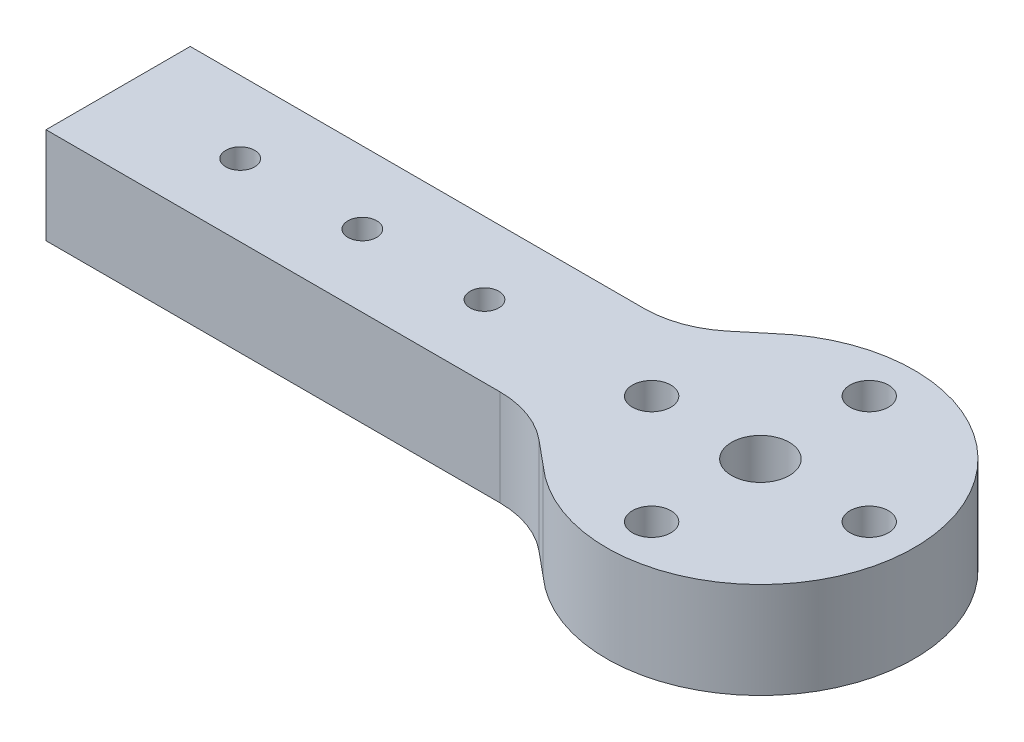
SolidWorks part; units mm, degrees
ref_plane "Front" through (0, 0, 0) normal (0, 0, 1) x (1, 0, 0)
ref_plane "Top" through (0, 0, 0) normal (0, 1, 0) x (1, 0, 0)
ref_plane "Right" through (0, 0, 0) normal (1, 0, 0) x (0, 0, -1)
sketch "Sketch1" plane through (0, 0, 0) normal (0, 1, 0) x (1, 0, 0)
  line L0 (23.1155, 15) -> (47.1915, 15)
  line L1 (0, 0) -> (50.8, 0)
  line L2 (0, 0) -> (0, 15)
  line L3 (0, 15) -> (23.1155, 15)
  line L4 (50.8, 0) -> (50.8, 15)
  line L5 (50.8, 7.5) -> (66.8, 7.5)
  line L6 (50.8, 0) -> (28.0325, 0)
  line L7 (53.577, 17.3042) -> (56.1261, 19.4192)
  line L8 (53.577, -2.3042) -> (56.1261, -4.4192)
  line L9 (0, 7.5) -> (50.8, 7.5)
  line L10 (25.4, 7.5) -> (50.8, 7.5)
  line L11 (25.4, 7.5) -> (0, 7.5)
  circle A2 centre (66.8, 7.5) radius 16
  circle A3 centre (66.8, 7.5) radius 11.3137
  circle A4 centre (25.4, 7.5) radius 1.5
  circle A5 centre (38.1, 7.5) radius 1.5
  circle A6 centre (12.7, 7.5) radius 1.5
  circle A7 centre (78.1137, 7.5) radius 2
  circle A8 centre (66.8, 18.8137) radius 2
  circle A9 centre (55.4863, 7.5) radius 2
  circle A10 centre (66.8, -3.8137) radius 2
  arc A11 (53.577, 17.3042) -> (47.1915, 15) centre (47.1915, 25) cw
  arc A12 (53.577, -2.3042) -> (47.1915, 0) centre (47.1915, -10) ccw
  circle A13 centre (66.8, 7.5) radius 3
  dimension "D4" = 10
  dimension "D1" = 50.8
  dimension "D2" = 15
  dimension "D3" = 16
extrude "Boss-Extrude1" add sketch "Sketch1" along normal blind 10
